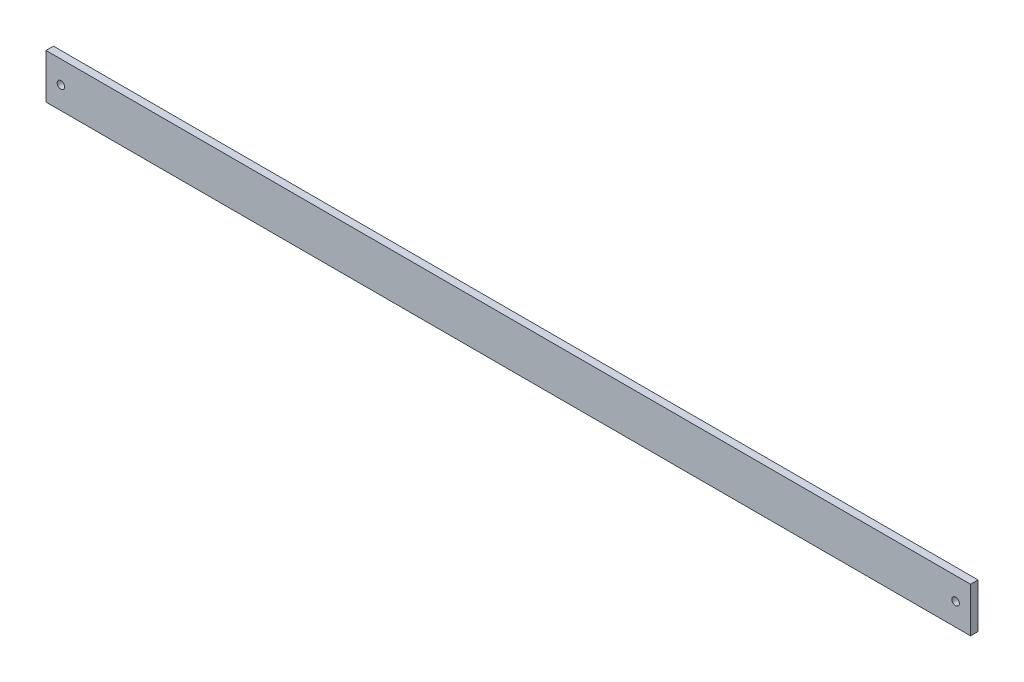
SolidWorks part; units mm, degrees
other "Markup1"
sketch "Sketch6" plane through (114.3, 38.1, 139.7) normal (0.0122, 0.8279, 0.5607) x (0.9984, -0.0412, 0.0392)
material "Balsa"
ref_plane "Front Plane" through (0, 0, 0) normal (0, 0, 1) x (1, 0, 0)
ref_plane "Top Plane" through (0, 0, 0) normal (0, 1, 0) x (1, 0, 0)
ref_plane "Right Plane" through (0, 0, 0) normal (1, 0, 0) x (0, 0, -1)
sketch "Sketch7" plane through (0, 0, 0) normal (0, 0, 1) x (1, 0, 0)
  line L1 (0, 0) -> (393.7, 0)
  line L2 (0, 0) -> (0, 19.05)
  line L3 (0, 19.05) -> (393.7, 19.05)
  line L4 (393.7, 0) -> (393.7, 19.05)
  circle A0 centre (6.35, 9.525) radius 1.5875
  circle A1 centre (387.35, 9.525) radius 1.5875
  dimension "Hole Diameter" = 3.175
  dimension "Hole Diameter2" = 3.175
  dimension "Width" = 19.05
  dimension "Total Length" = 393.7
  dimension "Hole Offset" = 6.35
  dimension "Length" = 381
extrude "Boss-Extrude1" add sketch "Sketch7" along normal blind 3.175
equation "\"Width@Sketch7\" = \"w\""
equation "\"L1\"= 15in"
equation "\"L2\"= 12.5in"
equation "\"L3\"= 15.207in"
equation "\"L4\"= 15in"
equation "\"LL\"= 30in"
equation "\"w\"= 0.75in"
equation "\"t\"= 0.125in"
equation "\"holeD\" = 0.125in"
equation "\"holeOffset\" = 0.25in"
equation "\"Total Length@Sketch7\" = \"L\" + 2 * \"holeOffset\""
equation "\"L\"= \"L1\""
equation "\"Hole Diameter@Sketch7\"= \"holeD\""
equation "\"Hole Diameter2@Sketch7\"= \"Hole Diameter@Sketch7\""
equation "\"Hole Offset@Sketch7\"= \"holeOffset\""
equation "\"Length@Sketch7\"= \"L\""
equation "\"Thickness@Boss-Extrude1\"= \"t\""
